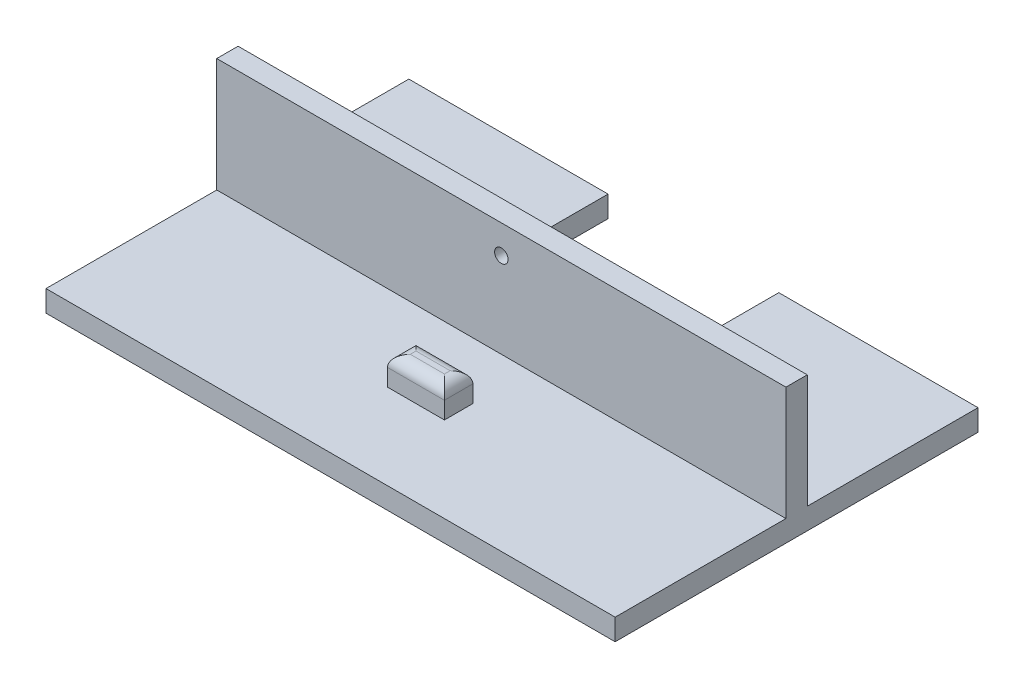
SolidWorks part; units mm, degrees
ref_plane "Front Plane" through (0, 0, 0) normal (0, 0, 1) x (1, 0, 0)
ref_plane "Top Plane" through (0, 0, 0) normal (0, 1, 0) x (1, 0, 0)
ref_plane "Right Plane" through (0, 0, 0) normal (1, 0, 0) x (0, 0, -1)
sketch "Sketch1" plane through (0, 0, 0) normal (1, 0, 0) x (0, 0, -1)
  line L0 (0, 0) -> (-42.8625, 0)
  line L1 (-42.8625, 0) -> (-42.8625, 4.7625)
  line L2 (-42.8625, 4.7625) -> (-4.7625, 4.7625)
  line L3 (-4.7625, 4.7625) -> (-4.7625, 30.1625)
  line L4 (-4.7625, 30.1625) -> (0, 30.1625)
  line L5 (0, 30.1625) -> (0, 0)
  line L7 (0, 0) -> (38.1, 0)
  line L8 (0, 0) -> (0, 4.7625)
  line L9 (0, 4.7625) -> (38.1, 4.7625)
  line L10 (38.1, 0) -> (38.1, 4.7625)
  dimension "D1" = 38.1
  dimension "D2" = 25.4
  dimension "D3" = 4.7625
  dimension "D4" = 38.1
extrude "Boss-Extrude1" add sketch "Sketch1" along normal blind 127 contours L5 L4 L3 L2 L1 L0 | L7 L10 L9 L5
sketch "Sketch2" plane through (0, 4.7625, 0) normal (0, 1, 0) x (1, 0, 0)
  line L0 (127, -42.8625) -> (0, -42.8625) construction
  line L1 (57.15, -23.8125) -> (69.85, -23.8125)
  line L2 (57.15, -23.8125) -> (57.15, -17.4625)
  line L3 (57.15, -17.4625) -> (69.85, -17.4625)
  line L4 (69.85, -23.8125) -> (69.85, -17.4625)
  line L7 (127, -4.7625) -> (0, -4.7625) construction
  point P4 (63.5, -23.8125)
  point P7 (63.5, -42.8625)
  dimension "D1" = 6.35
  dimension "D2" = 12.7
  dimension "D3" = 12.7
extrude "Boss-Extrude2" add sketch "Sketch2" along normal blind 6.35
sketch "Sketch3" plane through (0, 0, 4.7625) normal (0, 0, 1) x (1, 0, 0)
  line L0 (127, 30.1625) -> (0, 30.1625) construction
  line L1 (127, 4.7625) -> (0, 4.7625) construction
  circle A0 centre (63.5, 23.8125) radius 1.5
  point P5 (63.5, 30.1625)
  dimension "D1" = 3
  dimension "D2" = 19.05
extrude "Cut-Extrude1" cut sketch "Sketch3" against normal through all
fillet "Fillet1" radius 2.54 4 edges at (63.5, 11.1125, 17.4625) (69.85, 11.1125, 20.6375) (63.5, 11.1125, 23.8125) (57.15, 11.1125, 20.6375)
sketch "Sketch4" plane through (0, 4.7625, 0) normal (0, 1, 0) x (1, 0, 0)
  line L0 (127, 38.1) -> (0, 38.1) construction
  line L1 (44.45, 38.1) -> (82.55, 38.1)
  line L2 (44.45, 38.1) -> (44.45, 0)
  line L3 (44.45, 0) -> (82.55, 0)
  line L4 (82.55, 38.1) -> (82.55, 0)
  line L5 (127, 0) -> (0, 0) construction
  point P8 (-19.3946, 38.1)
  point P9 (-56.1353, 38.1)
  point P10 (63.5, 38.1)
  point P11 (63.5, 38.1)
  point P12 (42.3707, 0)
  dimension "D1" = 38.1
extrude "Cut-Extrude2" cut sketch "Sketch4" against normal through all
